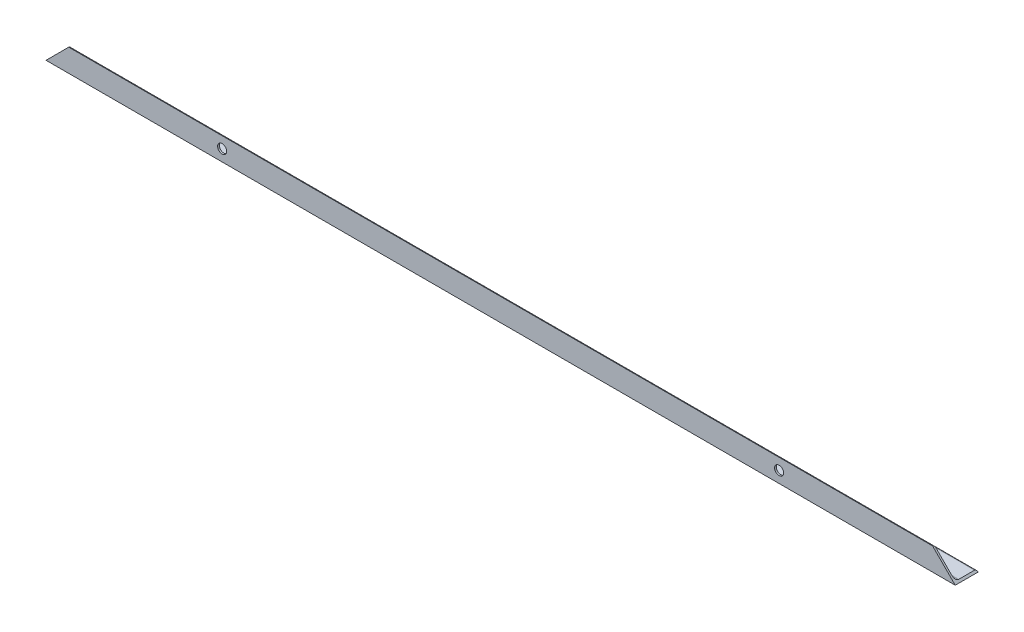
SolidWorks part; units mm, degrees
ref_plane "Front Plane" through (0, 0, 0) normal (0, 0, 1) x (1, 0, 0)
ref_plane "Top Plane" through (0, 0, 0) normal (0, 1, 0) x (1, 0, 0)
ref_plane "Right Plane" through (0, 0, 0) normal (1, 0, 0) x (0, 0, -1)
sketch "Sketch1" plane through (0, 0, 0) normal (0, 1, 0) x (1, 0, 0)
  line L0 (0, 0) -> (1600, 0)
  dimension "D1" = 1600
other "L angle (equal) 40X40X3(5)"
ref_plane "Plane1" through (0, 0, 0) normal (1, 0, 0) x (0, 0, -1)
sketch "Sketch13" plane through (0, 0, 0) normal (1, 0, 0) x (0, 0, -1)
  line L0 (0, 40) -> (0, 0)
  line L2 (3, 37) -> (3, 9)
  line L3 (9, 3) -> (37, 3)
  line L5 (40, 0) -> (0, 0)
  arc A0 (3, 37) -> (0, 40) centre (0, 37) ccw
  arc A1 (40, 0) -> (37, 3) centre (37, 0) ccw
  arc A2 (9, 3) -> (3, 9) centre (9, 9) cw
  point P8 (0, 20)
  point P9 (20, 0)
  point P10 (0, 0)
  dimension "Radius_2" = 3
  dimension "Radius_1" = 6
  dimension "V_leg" = 40
  dimension "H_leg" = 40
  dimension "thickness" = 3
sketch "Sketch14" plane through (0, 0, 0) normal (0, 0, 1) x (1, 0, 0)
  line L0 (1600, 0) -> (1600, 40)
  line L1 (0, 40) -> (0, 0)
  line L2 (40, 40) -> (0, 0)
  line L3 (1560, 40) -> (1600, 0)
  line L4 (0, 40) -> (0, 0)
  line L5 (0, 0) -> (1600, 0)
  line L6 (1600, 0) -> (1600, 40)
  line L7 (1600, 40) -> (0, 40)
  line L8 (0, 40) -> (0, 0) construction
  line L10 (1600, 0) -> (1600, 40) construction
  line L11 (1600, 40) -> (1560, 40)
  line L12 (40, 40) -> (0, 40)
  line L13 (40, 40) -> (1560, 40) construction
  line L14 (800, 40) -> (800, 0) construction
  line L15 (1600, 0) -> (0, 0) construction
  line L16 (310, 40) -> (310, 0) construction
  line L17 (1290, 40) -> (1290, 0) construction
  circle A1 centre (310, 20) radius 8
  circle A2 centre (1290, 20) radius 8
  dimension "D3" = 490
  dimension "D2" = 40
  dimension "D1" = 0
  dimension "D4" = 490
extrude "Cut-Extrude1" cut sketch "Sketch14" against normal through all
